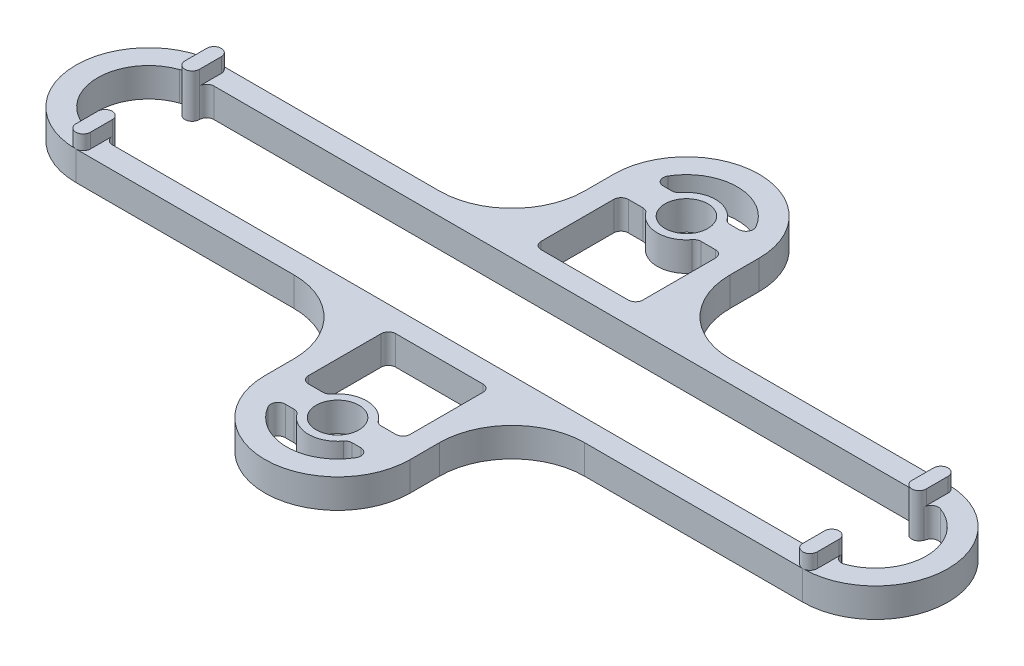
SolidWorks part; units mm, degrees
material "Stainless Steel (ferritic)"
ref_plane "Front Plane" through (0, 0, 0) normal (0, 0, 1) x (1, 0, 0)
ref_plane "Top Plane" through (0, 0, 0) normal (0, 1, 0) x (1, 0, 0)
ref_plane "Right Plane" through (0, 0, 0) normal (1, 0, 0) x (0, 0, -1)
sketch "Sketch1" plane through (0, 0, 0) normal (0, 1, 0) x (1, 0, 0)
  line L0 (-25, 0) -> (25, 0) construction
  line L1 (-25, 5) -> (-5, 5)
  line L2 (-25, -5) -> (-5, -5)
  line L3 (0, 12) -> (0, -12) construction
  line L4 (5, 12) -> (5, 5)
  line L5 (-5, 12) -> (-5, 5)
  line L6 (5, -5) -> (25, -5)
  line L7 (5, -5) -> (5, -12)
  line L8 (-5, -5) -> (-5, -12)
  line L9 (5, 5) -> (25, 5)
  arc A0 (-25, 5) -> (-25, -5) centre (-25, 0) ccw
  arc A1 (25, -5) -> (25, 5) centre (25, 0) ccw
  arc A2 (5, 12) -> (-5, 12) centre (0, 12) ccw
  arc A3 (-5, -12) -> (5, -12) centre (0, -12) ccw
  circle A4 centre (0, 12) radius 1
  circle A5 centre (0, -12) radius 1
  point P2 (0, 0)
  point P10 (0, 0)
  dimension "D5" = 2
  dimension "D1" = 10
  dimension "D2" = 50
  dimension "D3" = 24
  dimension "D4" = 10
extrude "Boss-Extrude1" add sketch "Sketch1" along normal blind 2
sketch "Sketch2" plane through (0, 2, 0) normal (0, 1, 0) x (1, 0, 0)
  line L0 (-25, 4.5) -> (-25, -4.5) construction
  line L1 (-24.5, 4.5) -> (-24.5, -4.5)
  line L2 (-25.5, 4.5) -> (-25.5, -4.5)
  line L3 (25, 4.5) -> (25, -4.5) construction
  line L4 (25.5, 4.5) -> (25.5, -4.5)
  line L5 (24.5, 4.5) -> (24.5, -4.5)
  line L6 (-5, 5) -> (-25, 5) construction
  arc A0 (-24.5, 4.5) -> (-25.5, 4.5) centre (-25, 4.5) ccw
  arc A1 (-25.5, -4.5) -> (-24.5, -4.5) centre (-25, -4.5) ccw
  arc A2 (25.5, 4.5) -> (24.5, 4.5) centre (25, 4.5) ccw
  arc A3 (24.5, -4.5) -> (25.5, -4.5) centre (25, -4.5) ccw
  arc A4 (25, -5) -> (25, 5) centre (25, 0) ccw construction
  point P2 (-25, 0)
  point P9 (25, 0)
  dimension "D1" = 1
extrude "Boss-Extrude2" add sketch "Sketch2" along normal blind 1
sketch "Sketch3" plane through (0, 2, 0) normal (0, 1, 0) x (1, 0, 0)
  line L0 (-24.5, -4.5) -> (-24.5, 4.5) construction
  line L1 (24.5, 3.5) -> (-24.5, 3.5)
  line L2 (24.5, 3.5) -> (24.5, -3.5)
  line L3 (24.5, -3.5) -> (-24.5, -3.5)
  line L4 (-24.5, 3.5) -> (-24.5, -3.5)
  line L5 (24.5, 3.5) -> (-24.5, -3.5) construction
  line L6 (24.5, -3.5) -> (-24.5, 3.5) construction
  line L7 (-5, 5) -> (-25, 5) construction
  line L9 (-25.5, 3.4641) -> (-25.5, -3.4641)
  line L10 (-25.5, 4.5) -> (-25.5, -4.5) construction
  line L11 (0, 0) -> (0, 21.0257) construction
  line L12 (25.5, 3.4641) -> (25.5, -3.4641)
  line L13 (-1.7321, 13) -> (-3.3541, 13)
  line L14 (1.7321, 13) -> (3.3541, 13)
  line L15 (0, 12) -> (-8.4552, 12) construction
  line L16 (-1.7321, 11) -> (-3.5, 11)
  line L17 (-3.5, 11) -> (-3.5, 5)
  line L18 (-3.5, 5) -> (3.5, 5)
  line L19 (3.5, 5) -> (3.5, 11)
  line L20 (3.5, 11) -> (1.7321, 11)
  line L21 (-5, 12) -> (-5, 5) construction
  line L22 (0, 0) -> (-32.6719, 0) construction
  line L23 (1.7321, -13) -> (3.3541, -13)
  line L24 (-1.7321, -13) -> (-3.3541, -13)
  line L25 (3.5, -11) -> (1.7321, -11)
  line L26 (-1.7321, -11) -> (-3.5, -11)
  line L27 (3.5, -5) -> (3.5, -11)
  line L28 (-3.5, -5) -> (3.5, -5)
  line L29 (-3.5, -11) -> (-3.5, -5)
  arc A1 (-25.5, 3.4641) -> (-25.5, -3.4641) centre (-25, 0) ccw
  arc A2 (-25, 5) -> (-25, -5) centre (-25, 0) ccw construction
  arc A3 (25.5, 3.4641) -> (25.5, -3.4641) centre (25, 0) cw
  arc A4 (3.3541, 13) -> (-3.3541, 13) centre (0, 12) ccw
  arc A5 (1.7321, 13) -> (-1.7321, 13) centre (0, 12) ccw
  arc A6 (1.7321, 11) -> (-1.7321, 11) centre (0, 12) cw
  arc A7 (3.3541, -13) -> (-3.3541, -13) centre (0, -12) cw
  arc A8 (1.7321, -13) -> (-1.7321, -13) centre (0, -12) cw
  arc A9 (1.7321, -11) -> (-1.7321, -11) centre (0, -12) ccw
  point P0 (0, 0)
  point P16 (-30, 0)
  point P17 (-28.5, 0)
  dimension "D5" = 4
  dimension "D1" = 1.5
  dimension "D2" = 0
  dimension "D3" = 0
  dimension "D4" = 1.5
  dimension "D6" = 1
  dimension "D7" = 1.5
extrude "Cut-Extrude1" cut sketch "Sketch3" against normal through all
fillet "Fillet2" radius 0.5 28 edges at (-25.5, 1, -3.4641) (-25.5, 1, 3.4641) (24.5, 1, 3.5) (24.5, 1, -3.5) (25.5, 1, -3.4641) (25.5, 1, 3.4641) (-24.5, 1, -3.5) (-24.5, 1, 3.5) (3.3541, 1, 13) (-1.7321, 1, 13) (1.7321, 1, 13) (-3.3541, 1, 13) (3.5, 1, 11) (-1.7321, 1, 11) (1.7321, 1, 11) (-3.5, 1, 11) (3.5, 1, 5) (-3.5, 1, 5) (-1.7321, 1, -11) (1.7321, 1, -11) (3.5, 1, -11) (3.5, 1, -5) (3.3541, 1, -13) (1.7321, 1, -13) (-1.7321, 1, -13) (-3.3541, 1, -13) (-3.5, 1, -5) (-3.5, 1, -11)
hole_wizard "#4 Clearance Hole1" positions "Sketch4" profile "Sketch5" hole size "#4" standard "ANSI Inch" end condition up to next
sketch "Sketch4" plane through (0, 0, 0) normal (0, -1, 0) x (-1, 0, 0)
  point P0 (0, 12)
  point P3 (0, -12)
sketch "Sketch5" plane through (0, 0, -12) normal (1, 0, 0) x (0, 0, -1)
  line L0 (0, 0) -> (0, 3)
  line L1 (0, 3) -> (1.4732, 3)
  line L2 (1.4732, 3) -> (1.4732, 0)
  line L5 (1.4732, 0) -> (0, 0)
  line L11 (0, -6.35) -> (0, 107.95) construction
  dimension "Thru Hole Dia." = 2.9464
  dimension "Thru Hole Depth" = 3
fillet "Fillet3" radius 5 4 edges at (-5, 1, 5) (5, 1, 5) (-5, 1, -5) (5, 1, -5)
sketch "Sketch6" plane through (0, 3, 0) normal (0, 1, 0) x (1, 0, 0)
  line L0 (-25.5, 3) -> (-25.5, -3)
  line L1 (-25, 3) -> (-25, -3) construction
  line L2 (-25, 0) -> (0, 0) construction
  line L3 (-25.5, 4.5) -> (-25.5, 2.8284) construction
  line L4 (-24.5, 3) -> (-24.5, -3)
  line L5 (-24.5, -4.5) -> (-24.5, 4.5) construction
  line L6 (0, 0) -> (0, 8.0752) construction
  line L7 (25, 3) -> (25, -3) construction
  line L8 (24.5, 3) -> (24.5, -3)
  line L9 (25.5, 3) -> (25.5, -3)
  arc A0 (-25.5, 3) -> (-24.5, 3) centre (-25, 3) ccw
  arc A1 (-24.5, -3) -> (-25.5, -3) centre (-25, -3) ccw
  arc A2 (24.5, -3) -> (25.5, -3) centre (25, -3) cw
  arc A3 (25.5, 3) -> (24.5, 3) centre (25, 3) cw
  dimension "D1" = 6
extrude "Cut-Extrude2" cut sketch "Sketch6" against normal through all
